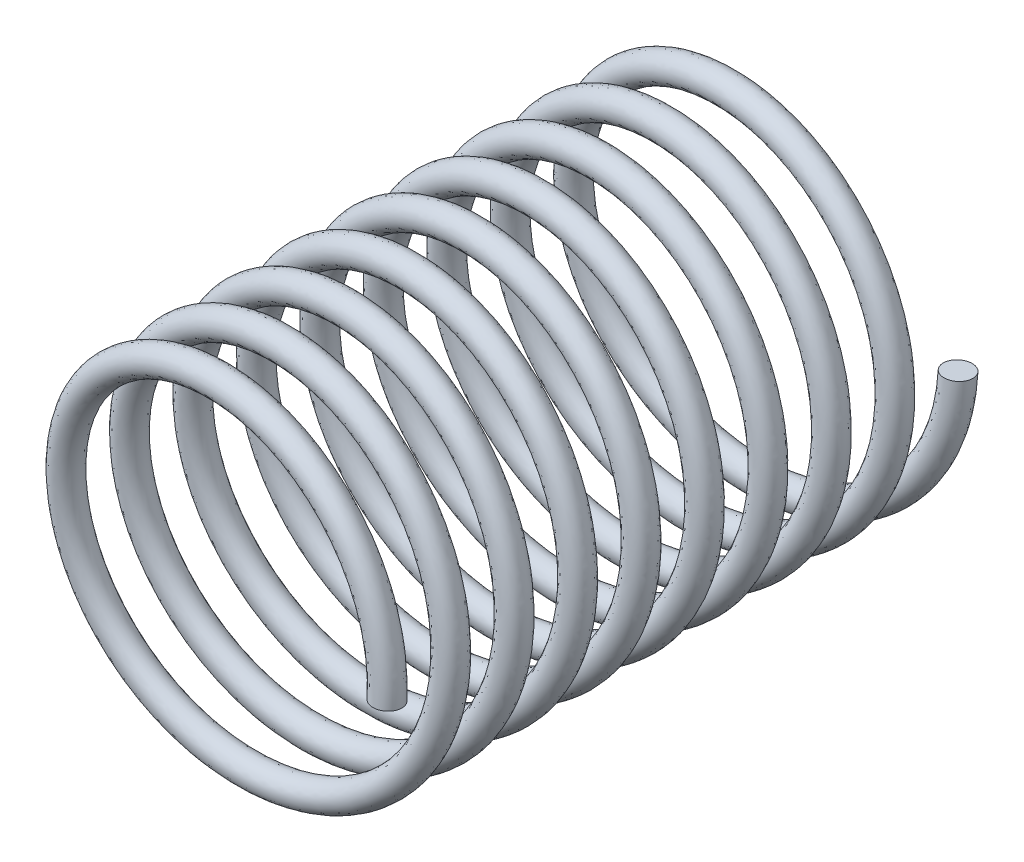
SolidWorks part; units mm, degrees
ref_plane "Front Plane" through (0, 0, 0) normal (0, 0, 1) x (1, 0, 0)
ref_plane "Top Plane" through (0, 0, 0) normal (0, 1, 0) x (1, 0, 0)
ref_plane "Right Plane" through (0, 0, 0) normal (1, 0, 0) x (0, 0, -1)
sketch "Sketch1" plane through (0, 0, 0) normal (0, 0, 1) x (1, 0, 0)
  circle A0 centre (0, 0) radius 25
  dimension "D1" = 50
curve "Helix/Spiral1" pitch 9 height 81 turns 9
ref_plane "Plane1" through (25, 0, 81) normal (0, -0.9984, 0.0572) x (-1, 0, 0)
sketch "Sketch3" plane through (25, 0, 81) normal (0, -0.9984, 0.0572) x (-1, 0, 0)
  circle A0 centre (0, 0) radius 2
  point P2 (0, 0)
  dimension "D1" = 4
sweep "Sweep1" add profiles "Sketch3" path "Helix/Spiral1"
